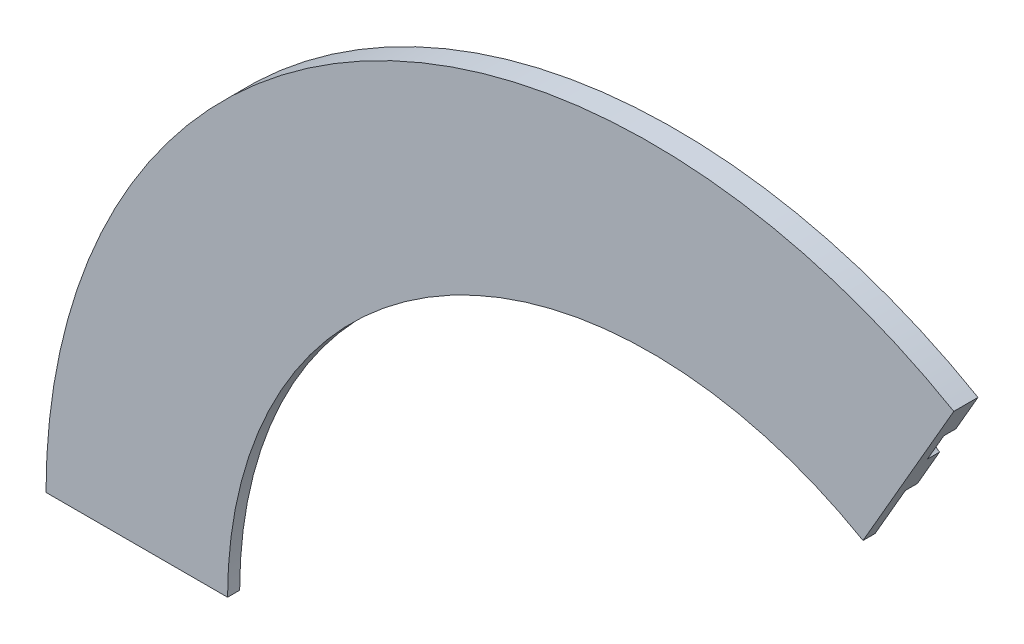
SolidWorks part; units mm, degrees
ref_plane "Alzado" through (0, 0, 0) normal (0, 0, 1) x (1, 0, 0)
ref_plane "Planta" through (0, 0, 0) normal (0, 1, 0) x (1, 0, 0)
ref_plane "Vista lateral" through (0, 0, 0) normal (1, 0, 0) x (0, 0, -1)
sketch "Croquis1" plane through (0, 0, 0) normal (0, 0, 1) x (1, 0, 0)
  circle A0 centre (0, 0) radius 200
  circle A1 centre (0, 0) radius 160
  circle A3 centre (145.6231, 105.8013) radius 5.4
  circle A4 centre (164.4382, 73.2126) radius 5.4
  circle A5 centre (176.0666, 37.4241) radius 5.4
  circle A6 centre (180, 0) radius 5.4
  circle A7 centre (176.0666, -37.4241) radius 5.4
  circle A8 centre (164.4382, -73.2126) radius 5.4
  circle A9 centre (145.6231, -105.8013) radius 5.4
  circle A10 centre (120.4435, -133.7661) radius 5.4
  circle A11 centre (90, -155.8846) radius 5.4
  circle A12 centre (55.6231, -171.1902) radius 5.4
  circle A13 centre (18.8151, -179.0139) radius 5.4
  circle A14 centre (-18.8151, -179.0139) radius 5.4
  circle A15 centre (-55.6231, -171.1902) radius 5.4
  circle A16 centre (-90, -155.8846) radius 5.4
  circle A17 centre (-120.4435, -133.7661) radius 5.4
  circle A18 centre (-145.6231, -105.8013) radius 5.4
  circle A19 centre (-164.4382, -73.2126) radius 5.4
  circle A20 centre (-176.0666, -37.4241) radius 5.4
  circle A21 centre (-180, 0) radius 5.4
  circle A22 centre (-176.0666, 37.4241) radius 5.4
  circle A23 centre (-164.4382, 73.2126) radius 5.4
  circle A24 centre (-145.6231, 105.8013) radius 5.4
  circle A25 centre (-120.4435, 133.7661) radius 5.4
  circle A26 centre (-90, 155.8846) radius 5.4
  circle A27 centre (-55.6231, 171.1902) radius 5.4
  circle A28 centre (-18.8151, 179.0139) radius 5.4
  circle A29 centre (18.8151, 179.0139) radius 5.4
  circle A30 centre (55.6231, 171.1902) radius 5.4
  circle A31 centre (90, 155.8846) radius 5.4
  circle A32 centre (120.4435, 133.7661) radius 5.4
extrude "Saliente-Extruir1" add sketch "Croquis1" along normal blind 4
sketch "Croquis2" plane through (0, 0, 4) normal (0, 0, 1) x (1, 0, 0)
  circle A0 centre (0, 0) radius 200
  circle A1 centre (0, 0) radius 140
extrude "Saliente-Extruir2" add sketch "Croquis2" along normal blind 4
sketch "Croquis3" plane through (0, 0, 0) normal (0, 0, -1) x (-1, 0, 0)
  line L0 (-100, 173.2051) -> (-166.2358, 173.2051)
  line L4 (-166.2358, 173.2051) -> (-252.1111, -105.1776)
  line L5 (-252.1111, -105.1776) -> (-104.7837, -222.5668)
  line L6 (-104.7837, -222.5668) -> (177.2656, -205.2342)
  line L7 (177.2656, -205.2342) -> (232.3124, -26.7886)
  line L8 (232.3124, -26.7886) -> (200, 0)
  line L9 (-100, 173.2051) -> (-70, 121.2436)
  line L10 (140, 0) -> (-70, 121.2436)
  line L13 (140, 0) -> (200, 0)
extrude "Cortar-Extruir1" cut sketch "Croquis3" against normal blind 10
